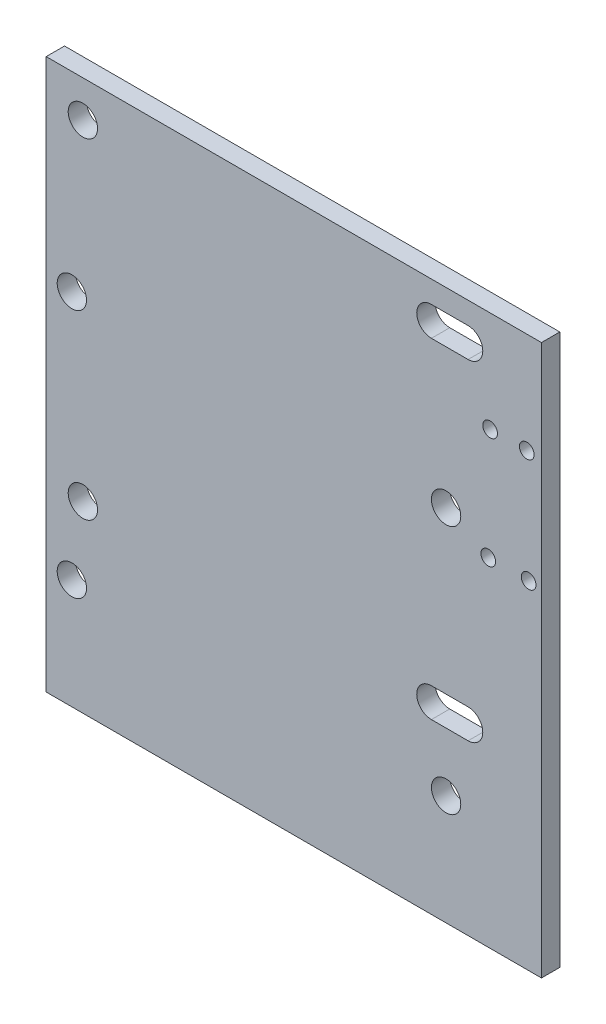
SolidWorks part; units mm, degrees
ref_plane "Front" through (0, 0, 0) normal (0, 0, 1) x (1, 0, 0)
ref_plane "Top" through (0, 0, 0) normal (0, 1, 0) x (1, 0, 0)
ref_plane "Right" through (0, 0, 0) normal (1, 0, 0) x (0, 0, -1)
sketch "Sketch1" plane through (0, 0, 0) normal (0, 0, 1) x (1, 0, 0)
  line L1 (-67.5, 75) -> (67.5, 75)
  line L2 (-67.5, 75) -> (-67.5, -75)
  line L3 (-67.5, -75) -> (67.5, -75)
  line L4 (67.5, 75) -> (67.5, -75)
  line L5 (-67.5, 75) -> (67.5, -75) construction
  line L6 (-67.5, -75) -> (67.5, 75) construction
  point P0 (0, 0)
  dimension "D1" = 135
  dimension "D2" = 150
extrude "Boss-Extrude1" add sketch "Sketch1" along normal blind 5
sketch "Sketch2" plane through (0, 0, 5) normal (0, 0, 1) x (1, 0, 0)
  line L0 (67.5, 75) -> (-67.5, 75) construction
  line L1 (-67.5, 75) -> (-67.5, -75) construction
  line L2 (-114.5449, 20) -> (116.0349, 20) construction
  line L3 (37.5, 65) -> (47.5, 65) construction
  line L4 (37.5, 69) -> (47.5, 69)
  line L5 (37.5, 61) -> (47.5, 61)
  line L7 (37.5, -25) -> (47.5, -25) construction
  line L8 (37.5, -29) -> (47.5, -29)
  line L9 (37.5, -21) -> (47.5, -21)
  circle A0 centre (-57.5, 65) radius 4
  arc A1 (37.5, 69) -> (37.5, 61) centre (37.5, 65) ccw
  arc A2 (37.5, -29) -> (37.5, -21) centre (37.5, -25) cw
  circle A3 centre (-57.5, -25) radius 4
  arc A4 (47.5, 61) -> (47.5, 69) centre (47.5, 65) ccw
  arc A5 (47.5, -21) -> (47.5, -29) centre (47.5, -25) cw
  point P14 (42.5, 65)
  point P21 (42.5, -25)
  dimension "D1" = 8
  dimension "D2" = 10
  dimension "D3" = 10
  dimension "D4" = 4
  dimension "D6" = 10
  dimension "D5" = 45
  dimension "D7" = 110
extrude "Cut-Extrude1" cut sketch "Sketch2" against normal up to next
sketch "Sketch4" plane through (0, 0, 5) normal (0, 0, 1) x (1, 0, 0)
  circle A0 centre (44.55, 40.25) radius 2.35
  circle A1 centre (16.45, 40.25) radius 2.35
  circle A2 centre (-33.45, 40.25) radius 2.35
  circle A3 centre (-61.55, 40.25) radius 2.35
  circle A4 centre (-61.55, -62.75) radius 2.35
  circle A5 centre (-33.45, -62.75) radius 2.35
  circle A6 centre (44.55, -62.75) radius 2.35
  circle A7 centre (16.45, -62.75) radius 2.35
extrude "Cut-Extrude3" [suppressed] cut sketch "Sketch4" against normal through all
sketch "Sketch6" plane through (0, 0, 5) normal (0, 0, 1) x (1, 0, 0)
  line L1 (-67.5, 75) -> (-67.5, -75) construction
  circle A0 centre (-60.5, 23) radius 4
  circle A1 centre (-60.5, -45) radius 4
  circle A2 centre (41.5, 23) radius 4
  circle A3 centre (41.5, -45) radius 4
  circle A10 centre (-57.5, -25) radius 4 construction
  dimension "D1" = 8
  dimension "D2" = 8
  dimension "D3" = 8
  dimension "D4" = 8
  dimension "D8" = 68
  dimension "D9" = 20
  dimension "D5" = 102
  dimension "D6" = 102
  dimension "D7" = 7
extrude "Cut-Extrude5" cut sketch "Sketch6" against normal up to next
sketch "Sketch7" plane through (0, 0, 0) normal (0, 0, -1) x (-1, 0, 0)
  line L1 (-37.5, 69) -> (-47.5, 69) construction
  circle A0 centre (-63.5, 47.5) radius 2
  circle A1 centre (-53.5, 47.5) radius 2
  circle A2 centre (-64, 17) radius 2
  circle A3 centre (-53, 17) radius 2
  dimension "D1" = 4
  dimension "D2" = 4
  dimension "D3" = 4
  dimension "D4" = 4
extrude "Cut-Extrude6" cut sketch "Sketch7" against normal up to next
